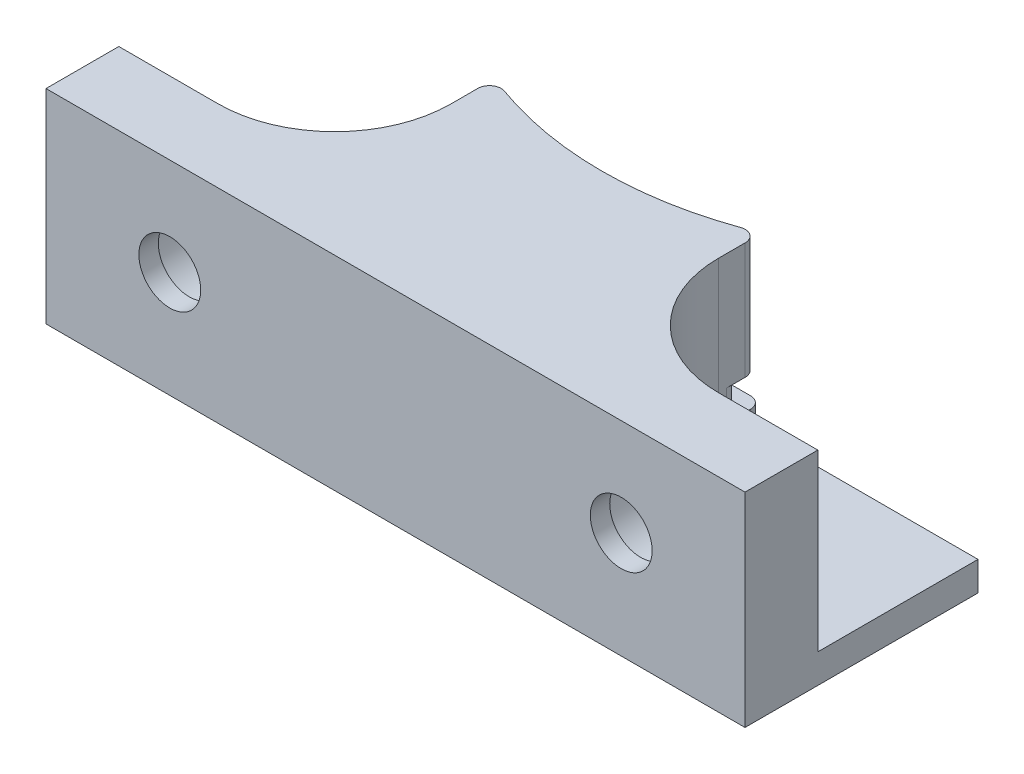
SolidWorks part; units mm, degrees
other "Markup1"
sketch "Sketch4" plane through (-125.7365, 25.4, -65.9837) normal (-0.2855, 0.1861, -0.9401) x (-0.9569, -0.1093, 0.269)
ref_plane "Front Plane" through (0, 0, 0) normal (0, 0, 1) x (1, 0, 0)
ref_plane "Top Plane" through (0, 0, 0) normal (0, 1, 0) x (1, 0, 0)
ref_plane "Right Plane" through (0, 0, 0) normal (1, 0, 0) x (0, 0, -1)
sketch "Sketch1" plane through (0, 0, 0) normal (0, 1, 0) x (1, 0, 0)
  line L0 (29.1508, 25.4) -> (0, 95.7762) construction
  line L1 (76.2, 25.4) -> (-76.2, 25.4)
  line L2 (76.2, 25.4) -> (76.2, -25.4)
  line L3 (76.2, -25.4) -> (-76.2, -25.4)
  line L4 (-76.2, 25.4) -> (-76.2, -25.4)
  line L5 (76.2, 25.4) -> (-76.2, -25.4) construction
  line L6 (76.2, -25.4) -> (-76.2, 25.4) construction
  line L7 (0, 95.7762) -> (-29.1508, 25.4) construction
  arc A0 (-29.1508, 25.4) -> (29.1508, 25.4) centre (0, 95.7762) ccw
  point P0 (0, 0)
  dimension "D1" = 76.1746
  dimension "D2" = 45
  dimension "D3" = 152.4
  dimension "D4" = 50.8
extrude "Boss-Extrude1" add sketch "Sketch1" along normal blind 25.4 contours A0 L1 L4 L3 L2
sketch "Sketch2" plane through (0, 0, 0) normal (0, -1, 0) x (1, 0, 0)
  line L1 (-76.2, 25.4) -> (76.2, 25.4)
  line L6 (-76.2, 25.4) -> (-76.2, -21.59)
  line L7 (-76.2, -25.4) -> (-76.2, 25.4) construction
  line L8 (-76.2, -21.59) -> (-29.9669, -21.59)
  line L9 (76.2, 25.4) -> (76.2, -21.59)
  line L10 (76.2, -21.59) -> (29.9669, -21.59)
  line L11 (-29.1508, -25.4) -> (-76.2, -25.4) construction
  arc A1 (-29.9669, -21.59) -> (29.9669, -21.59) centre (0, -95.7762) cw
  arc A3 (29.1508, -25.4) -> (-29.1508, -25.4) centre (0, -95.7762) ccw construction
  dimension "D1" = 80.01
  dimension "D2" = 3.81
extrude "Boss-Extrude2" add sketch "Sketch2" along normal blind 6.604
sketch "Sketch3" plane through (0, -6.604, 0) normal (0, -1, 0) x (1, 0, 0)
  line L0 (76.2, -21.59) -> (76.2, 25.4) construction
  line L1 (-76.2, 25.4) -> (76.2, 25.4)
  line L2 (-76.2, 25.4) -> (-76.2, -25.4)
  line L3 (-76.2, -25.4) -> (76.2, -25.4)
  line L4 (76.2, 25.4) -> (76.2, -25.4)
  line L5 (76.2, -25.4) -> (29.1508, -25.4) construction
extrude "Boss-Extrude3" add sketch "Sketch3" along normal blind 12.446
sketch "Sketch5" plane through (0, 25.4, 0) normal (0, 1, 0) x (1, 0, 0)
  line L0 (-29.1508, 25.4) -> (-29.1508, -9.525)
  line L1 (-29.1508, -9.525) -> (-76.2, -9.525)
  line L2 (-76.2, 25.4) -> (-76.2, -25.4) construction
  line L3 (-76.2, -9.525) -> (-76.2, 25.4)
  line L4 (-76.2, 25.4) -> (76.2, 25.4)
  line L5 (76.2, 25.4) -> (76.2, -9.525)
  line L6 (76.2, -9.525) -> (29.1508, -9.525)
  line L7 (29.1508, -9.525) -> (29.1508, 25.4)
  line L8 (76.2, 25.4) -> (76.2, -25.4) construction
  line L9 (-29.1508, 25.4) -> (-76.2, 25.4) construction
  line L10 (76.2, -25.4) -> (-76.2, -25.4) construction
  arc A0 (-29.1508, 25.4) -> (29.1508, 25.4) centre (0, 95.7762) ccw
  arc A3 (-29.1508, 25.4) -> (29.1508, 25.4) centre (0, 95.7762) ccw construction
  line M8 (-29.1508, 25.4) -> (-76.2, 25.4)
  line M9 (-76.2, 25.4) -> (-76.2, -25.4)
  line M11 (76.2, -25.4) -> (76.2, 25.4)
  line M12 (76.2, 25.4) -> (29.1508, 25.4)
  dimension "D1" = 15.875
extrude "Cut-Extrude1" cut sketch "Sketch5" against normal offset from surface (38.1 mm away) 6.35 contours L1 L0 M8 M9 | L7 L6 M11 M12 up to face at (0, -19.05, 0)
fillet "Fillet1" radius 2.54 6 edges at (29.1508, -9.652, -25.4) (-29.1508, -9.652, -25.4) (-29.1508, -3.302, -21.2655) (29.1508, -3.302, -21.2655) (29.1508, 12.7, -25.4) (-29.1508, 12.7, -25.4)
fillet "Fillet2" radius 25.4 2 edges at (29.1508, 6.35, 9.525) (-29.1508, 6.35, 9.525)
sketch "Sketch6" plane through (0, 0, 0) normal (0, 0, 1) x (1, 0, 0)
  line L0 (49.2125, 4.191) -> (-49.2125, 4.191) construction
  line L1 (29.1508, -19.05) -> (79.9508, -19.05) construction
  circle A0 centre (49.2125, 4.191) radius 9.9187
  circle A1 centre (-49.2125, 4.191) radius 9.9187
  point P4 (0, 4.191)
  dimension "D1" = 98.425
  dimension "D3" = 19.8374
  dimension "D2" = 23.241
extrude "Cut-Extrude2" cut sketch "Sketch6" along normal offset from surface 4.2418 and the other way through all from surface at 9.525 up to face at (0, 3.175, 25.4) starting at face at (65.3754, 6.35, 9.525)
sketch "Sketch7" plane through (0, 0, 21.1582) normal (0, 0, -1) x (-1, 0, 0)
  circle A0 centre (-49.2125, 4.191) radius 6.7437
  circle A1 centre (49.2125, 4.191) radius 6.7437
  arc A2 (-54.5508, -4.1686) -> (-54.5508, 12.5506) centre (-49.2125, 4.191) ccw construction
  circle A3 centre (49.2125, 4.191) radius 9.9187 construction
  dimension "D1" = 13.4874
extrude "Cut-Extrude3" cut sketch "Sketch7" against normal through all
